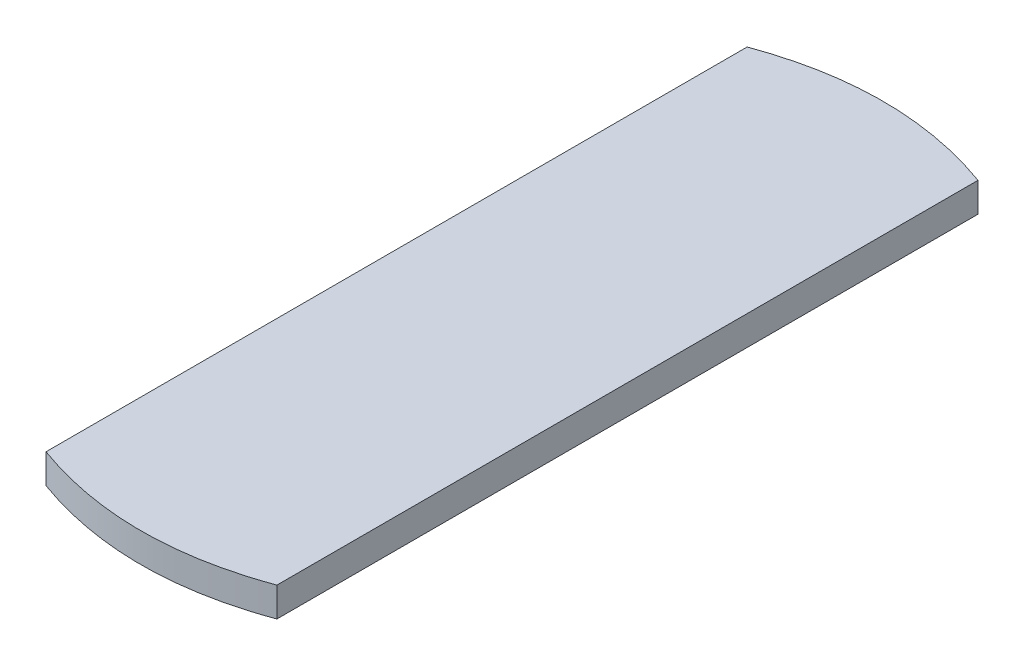
SolidWorks part; units mm, degrees
ref_plane "Front Plane" through (0, 0, 0) normal (0, 0, 1) x (1, 0, 0)
ref_plane "Top Plane" through (0, 0, 0) normal (0, 1, 0) x (1, 0, 0)
ref_plane "Right Plane" through (0, 0, 0) normal (1, 0, 0) x (0, 0, -1)
sketch "Sketch1" plane through (0, 0, 0) normal (0, 1, 0) x (1, 0, 0)
  line L0 (-27.5, 83.5) -> (-0.2985, 93.5) construction
  line L1 (-27.5, 83.5) -> (27.5, 83.5)
  line L2 (-27.5, 83.5) -> (-27.5, -83.5)
  line L3 (-27.5, -83.5) -> (27.5, -83.5)
  line L4 (27.5, 83.5) -> (27.5, -83.5)
  line L5 (-27.5, 83.5) -> (27.5, -83.5) construction
  line L6 (-27.5, -83.5) -> (27.5, 83.5) construction
  line L7 (-0.2985, 93.5) -> (27.5, 83.5) construction
  line L8 (-27.5, -83.5) -> (0.1858, -93.5) construction
  line L9 (0.1858, -93.5) -> (27.5, -83.5) construction
  spline S0 degree 2 poles (-27.5, 83.5) (-0.2985, 93.5) (27.5, 83.5) knots 0 0 0 1 1 1
  spline S1 degree 2 poles (-27.5, -83.5) (0.1858, -93.5) (27.5, -83.5) knots 0 0 0 1 1 1
  point P0 (0, 0)
  dimension "D1" = 55
  dimension "D2" = 167
  dimension "D3" = 10
  dimension "D4" = 10
extrude "Boss-Extrude1" add sketch "Sketch1" along normal blind 7 contours S0 L1 | L4 L1 L2 L3 | L3 S1
